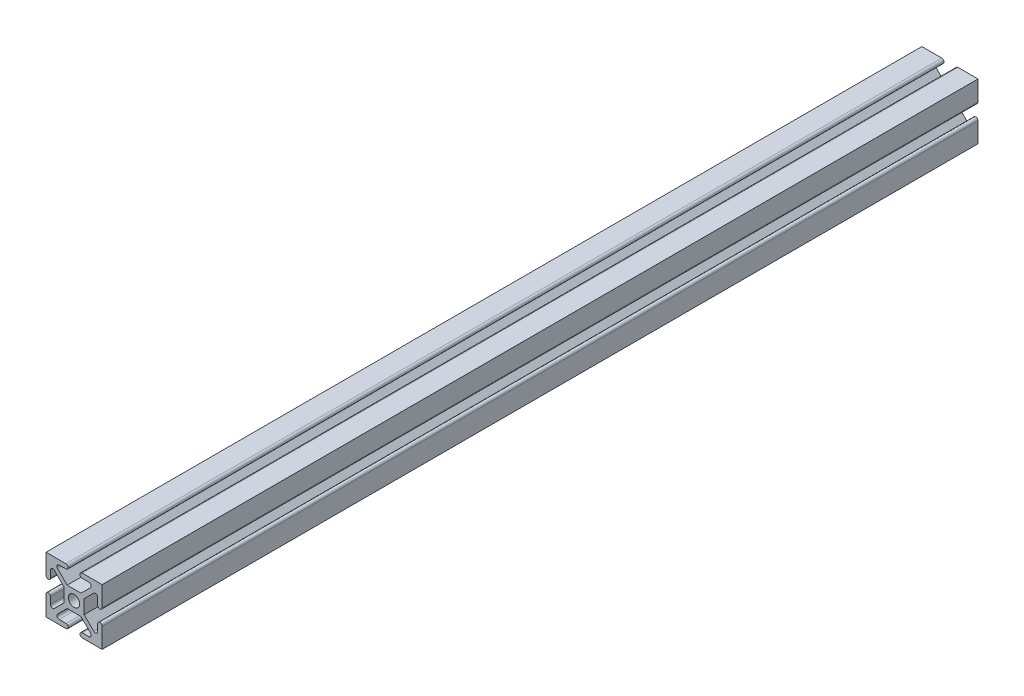
SolidWorks part; units mm, degrees
ref_plane "Front Plane" through (0, 0, 0) normal (0, 0, 1) x (1, 0, 0)
ref_plane "Top Plane" through (0, 0, 0) normal (0, 1, 0) x (1, 0, 0)
ref_plane "Right Plane" through (0, 0, 0) normal (1, 0, 0) x (0, 0, -1)
sketch "Sketch2" plane through (0, 0, 0) normal (0, 0, 1) x (1, 0, 0)
  line L0 (9.4142, 17) -> (5.1716, 21.2426)
  line L5 (9.4142, 17) -> (12.5, 17)
  line L9 (5.8995, 23) -> (8.8995, 23)
  line L10 (8.8995, 25) -> (0, 25)
  line L11 (0, 25) -> (8.8995, 25)
  line L12 (0, 16.1005) -> (0, 25)
  line L13 (2, 19.1005) -> (2, 16.1005)
  line L14 (8, 15.5858) -> (3.7574, 19.8284)
  line L15 (0, 25) -> (35355.3391, -35330.3391) construction
  line L16 (12.5, 12.5) -> (35367.8391, 35367.8391) construction
  line L17 (12.6363, 12.5) -> (50012.6363, 12.5) construction
  line L18 (12.5, 12.3637) -> (12.5, 50012.3637) construction
  line L19 (8, 15.5858) -> (8, 12.5)
  line L20 (9.4142, 8) -> (12.5, 8)
  line L21 (9.4142, 8) -> (5.1716, 3.7574)
  line L22 (5.8995, 2) -> (8.8995, 2)
  line L23 (8.8995, 0) -> (0, 0)
  line L24 (0, 8.8995) -> (0, 0)
  line L25 (2, 5.8995) -> (2, 8.8995)
  line L26 (8, 9.4142) -> (8, 12.5)
  line L27 (8, 9.4142) -> (3.7574, 5.1716)
  line L28 (15.5858, 17) -> (12.5, 17)
  line L29 (15.5858, 17) -> (19.8284, 21.2426)
  line L30 (19.1005, 23) -> (16.1005, 23)
  line L31 (16.1005, 25) -> (25, 25)
  line L32 (25, 16.1005) -> (25, 25)
  line L33 (23, 19.1005) -> (23, 16.1005)
  line L34 (17, 15.5858) -> (21.2426, 19.8284)
  line L35 (17, 15.5858) -> (17, 12.5)
  line L36 (17, 9.4142) -> (17, 12.5)
  line L37 (15.5858, 8) -> (12.5, 8)
  line L38 (17, 9.4142) -> (21.2426, 5.1716)
  line L39 (23, 5.8995) -> (23, 8.8995)
  line L40 (25, 8.8995) -> (25, 0)
  line L41 (16.1005, 0) -> (25, 0)
  line L42 (19.1005, 2) -> (16.1005, 2)
  line L43 (15.5858, 8) -> (19.8284, 3.7574)
  arc A0 (5.1716, 21.2426) -> (5.8995, 23) centre (5.8995, 21.9706) cw
  arc A1 (0, 16.1005) -> (2, 16.1005) centre (1, 16.1005) ccw
  arc A2 (8.8995, 25) -> (8.8995, 23) centre (8.8995, 24) cw
  arc A3 (3.7574, 19.8284) -> (2, 19.1005) centre (3.0294, 19.1005) ccw
  arc A4 (5.1716, 3.7574) -> (5.8995, 2) centre (5.8995, 3.0294) ccw
  arc A5 (8.8995, 0) -> (8.8995, 2) centre (8.8995, 1) ccw
  arc A6 (0, 8.8995) -> (2, 8.8995) centre (1, 8.8995) cw
  arc A7 (3.7574, 5.1716) -> (2, 5.8995) centre (3.0294, 5.8995) cw
  arc A8 (19.8284, 21.2426) -> (19.1005, 23) centre (19.1005, 21.9706) ccw
  arc A9 (16.1005, 25) -> (16.1005, 23) centre (16.1005, 24) ccw
  arc A10 (25, 16.1005) -> (23, 16.1005) centre (24, 16.1005) cw
  arc A11 (21.2426, 19.8284) -> (23, 19.1005) centre (21.9706, 19.1005) cw
  arc A12 (19.8284, 3.7574) -> (19.1005, 2) centre (19.1005, 3.0294) cw
  arc A13 (21.2426, 5.1716) -> (23, 5.8995) centre (21.9706, 5.8995) ccw
  arc A14 (25, 8.8995) -> (23, 8.8995) centre (24, 8.8995) ccw
  arc A15 (16.1005, 0) -> (16.1005, 2) centre (16.1005, 1) cw
  circle A16 centre (12.5, 12.5) radius 2.5
  dimension "D14" = 5
  dimension "D2" = 1.0294
  dimension "D3" = 12.5
  dimension "D4" = 12.5
  dimension "D5" = 17.6777
  dimension "D7" = 45
  dimension "D9" = 12.5
  dimension "D10" = 6
  dimension "D11" = 3
  dimension "D12" = 1
  dimension "D13" = 2
extrude "Boss-Extrude1" add sketch "Sketch2" along normal blind 390 contours A15 L41 L40 A14 L39 A13 L38 L36 L35 L34 A11 L33 A10 L32 L31 A9 L30 A8 L29 L28 L5 L0 A0 L9 A2 L10 L12 A1 L13 A3 L14 L19 L26 L27 A7 L25 A6 L24 L23 A5 L22 A4 L21 L20 L37 L43 A12 L42 A16
